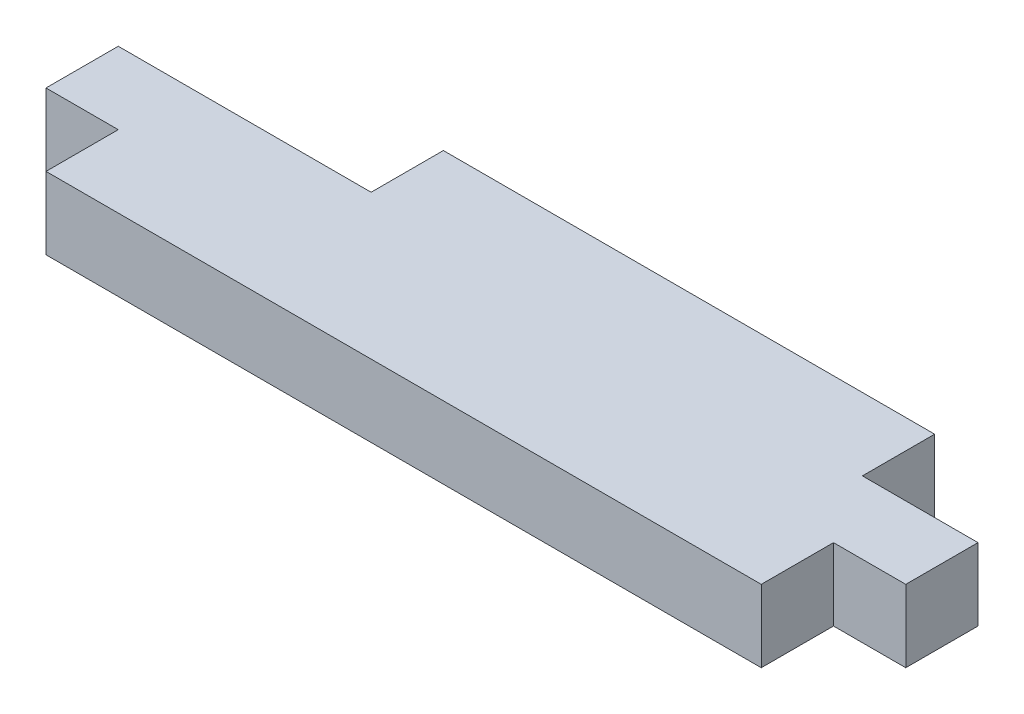
SolidWorks part; units mm, degrees
ref_plane "Front Plane" through (0, 0, 0) normal (0, 0, 1) x (1, 0, 0)
ref_plane "Top Plane" through (0, 0, 0) normal (0, 1, 0) x (1, 0, 0)
ref_plane "Right Plane" through (0, 0, 0) normal (1, 0, 0) x (0, 0, -1)
sketch "Sketch1" plane through (0, 0, 0) normal (0, 0, 1) x (1, 0, 0)
  line L1 (88.394, -121) -> (28.894, -121)
  line L2 (88.394, -121) -> (88.394, -126)
  line L3 (88.394, -126) -> (28.894, -126)
  line L4 (28.894, -121) -> (28.894, -126)
extrude "Boss-Extrude1" add sketch "Sketch1" along normal blind 5
sketch "Sketch2" plane through (0, 0, 5) normal (0, 0, 1) x (1, 0, 0)
  line L0 (88.394, -121) -> (28.894, -121) construction
  line L1 (33.894, -121) -> (83.394, -121)
  line L2 (33.894, -121) -> (33.894, -126)
  line L3 (33.894, -126) -> (83.394, -126)
  line L4 (83.394, -121) -> (83.394, -126)
  line L5 (33.894, -131) -> (33.894, -121) construction
  line L6 (28.894, -126) -> (88.394, -126) construction
  line L7 (83.394, -100) -> (83.394, -153) construction
extrude "Boss-Extrude2" add sketch "Sketch2" along normal blind 5
sketch "Sketch3" plane through (0, 0, 0) normal (0, 0, -1) x (-1, 0, 0)
  line L0 (-28.894, -126) -> (-88.394, -126) construction
  line L3 (-46.394, -126) -> (-80.394, -126)
  line L4 (-46.394, -126) -> (-46.394, -121)
  line L5 (-46.394, -121) -> (-80.394, -121)
  line L6 (-80.394, -126) -> (-80.394, -121)
  line L7 (-46.394, -153) -> (-46.394, -121) construction
  line L8 (-88.394, -121) -> (-28.894, -121) construction
  line L9 (-80.394, -150) -> (-80.394, -121) construction
extrude "Boss-Extrude3" add sketch "Sketch3" along normal blind 5
